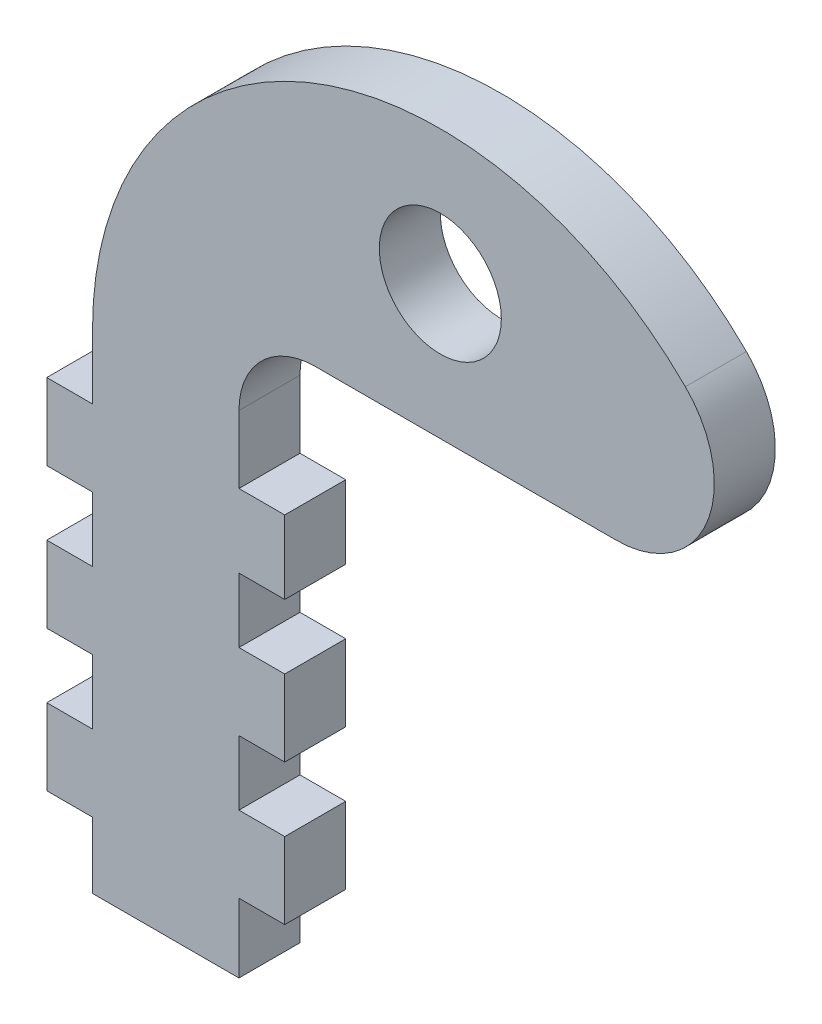
SolidWorks part; units mm, degrees
ref_plane "前视基准面" through (0, 0, 0) normal (0, 0, 1) x (1, 0, 0)
ref_plane "上视基准面" through (0, 0, 0) normal (0, 1, 0) x (1, 0, 0)
ref_plane "右视基准面" through (0, 0, 0) normal (1, 0, 0) x (0, 0, -1)
sketch "草图1" plane through (0, 0, 0) normal (0, 0, 1) x (1, 0, 0)
  line L0 (0, 0) -> (0, 33.1575) construction
  line L1 (2.9146, -70.7414) -> (-63.9065, -70.7414) construction
  line L2 (-4.8, -70.7414) -> (-4.8, 24.5127) construction
  line L3 (4.8, -70.7414) -> (4.8, 24.5127) construction
  line L4 (-4.8, -14) -> (-4.8, -18.23)
  line L5 (4.8, -13.8) -> (4.8, -18.23)
  line L6 (-7.8, -70.7414) -> (-7.8, -48.8799) construction
  line L7 (7.8, -70.5751) -> (7.8, -48.6799) construction
  line L8 (-4.8, -46.02) -> (4.8, -46.02)
  line L9 (-4.8, -41.69) -> (-7.8, -41.69)
  line L10 (-7.8, -41.69) -> (-7.8, -36.69)
  line L11 (-7.8, -36.69) -> (-4.8, -36.69)
  line L12 (4.8, -41.49) -> (4.8, -46.02)
  line L13 (-4.8, -32.46) -> (-7.8, -32.46)
  line L14 (-7.8, -32.46) -> (-7.8, -27.46)
  line L15 (-7.8, -27.46) -> (-4.8, -27.46)
  line L16 (-4.7842, -23.23) -> (-7.8, -23.23)
  line L17 (-7.8, -23.23) -> (-7.8, -18.23)
  line L18 (-7.8, -18.23) -> (-4.8, -18.23)
  line L19 (4.8, -18.23) -> (7.8, -18.23)
  line L20 (7.8, -18.23) -> (7.8, -23.03)
  line L21 (7.8, -23.03) -> (4.8, -23.03)
  line L22 (4.8, -23.03) -> (4.8, -27.26)
  line L23 (4.8, -27.26) -> (7.8, -27.26)
  line L24 (7.8, -27.26) -> (7.8, -32.26)
  line L25 (7.8, -32.26) -> (4.8, -32.26)
  line L26 (4.8, -32.26) -> (4.8, -36.49)
  line L27 (4.8, -36.49) -> (7.8, -36.49)
  line L28 (7.8, -36.49) -> (7.8, -41.49)
  line L29 (7.8, -41.49) -> (4.8, -41.49)
  line L30 (-4.8, -23.23) -> (-4.8, -27.46)
  line L31 (-4.8, -41.69) -> (-4.8, -46.02)
  line L32 (4.8, -32.26) -> (4.8, -36.49)
  line L33 (4.8, -23.03) -> (4.8, -27.26)
  line L34 (-4.8, -32.46) -> (-4.8, -36.69)
  line L35 (0, 0) -> (36.2449, 0) construction
  line L36 (9.8, -8.8) -> (18, -8.8)
  line L37 (18, 0) -> (18, 24.4333) construction
  line L38 (18, -8.8) -> (29.4809, -8.8)
  circle A0 centre (18, 0) radius 4
  arc A2 (4.8, -13.8) -> (9.8, -8.8) centre (9.8, -13.8) cw
  arc A3 (-4.8, -14) -> (34.0643, 2.1796) centre (18, -14) cw
  arc A4 (29.4809, -8.8) -> (34.0643, 2.1796) centre (29.5393, -2.3779) ccw
  point P5 (0, -14)
  point P7 (0, -34)
  point P8 (0, -54)
  point P13 (4.8, -70.7414)
  point P14 (-4.8, -70.7414)
  point P21 (0, -46.02)
  point P22 (-7.8, -70.7414)
  point P23 (7.8, -70.7751)
  point P27 (-4.8, -46.02)
  point P30 (-4.8, -14)
  point P31 (-4.8, -18.23)
  point P32 (-4.7842, -23.23)
  point P33 (-4.8, -27.46)
  point P34 (-4.8, -32.46)
  point P35 (-4.8, -36.69)
  point P36 (-4.8, -41.69)
  point P63 (18, 0)
  dimension "D4" = 9.6
  dimension "D17" = 14
  dimension "D2" = 20
  dimension "D3" = 20
  dimension "D5" = 12.02
  dimension "D6" = 7.8
  dimension "D7" = 7.8
  dimension "D8" = 32.02
  dimension "D9" = 4.23
  dimension "D10" = 5
  dimension "D11" = 4.23
  dimension "D12" = 5
  dimension "D13" = 4.23
  dimension "D14" = 5
  dimension "D15" = 4.33
  dimension "D16" = 18
extrude "凸台-拉伸1" add sketch "草图1" along normal blind 4
